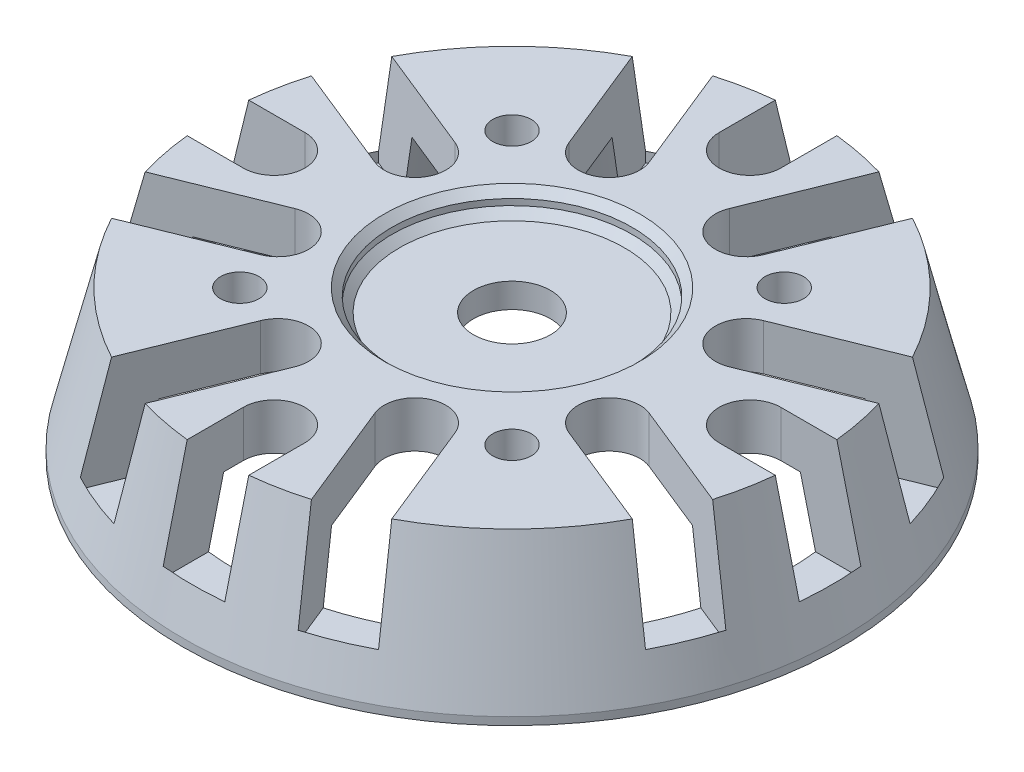
SolidWorks part; units mm, degrees
ref_plane "前视基准面" through (0, 0, 0) normal (0, 0, 1) x (1, 0, 0)
ref_plane "上视基准面" through (0, 0, 0) normal (0, 1, 0) x (1, 0, 0)
ref_plane "右视基准面" through (0, 0, 0) normal (1, 0, 0) x (0, 0, -1)
sketch "草图1" plane through (0, 0, 0) normal (0, 1, 0) x (1, 0, 0)
  circle A0 centre (0, 0) radius 21.4
  dimension "D1" = 42.8
extrude "凸台-拉伸2" add sketch "草图1" along normal blind 0.5 contours A0
sketch "草图3" plane through (0, 0.5, 0) normal (0, 1, 0) x (1, 0, 0)
  circle A0 centre (0, 0) radius 21.4
ref_plane "基准面1" through (0, 9.5, 0) normal (0, 1, 0) x (1, 0, 0)
sketch "草图6" plane through (0, 9.5, 0) normal (0, 1, 0) x (1, 0, 0)
  circle A0 centre (0, 0) radius 19.2
  dimension "D1" = 38.4
loft "放样1" add profiles "草图6" section "草图6" section face at (0, 0.5, 21.4)
shell "抽壳1" thickness 3
sketch "草图7" plane through (0, 9.5, 0) normal (0, 1, 0) x (1, 0, 0)
  circle A0 centre (0, 0) radius 2.5
  dimension "D1" = 5
extrude "切除-拉伸1" cut sketch "草图7" against normal through all
sketch "草图8" plane through (0, 9.5, 0) normal (0, 1, 0) x (1, 0, 0)
  circle A0 centre (0, 0) radius 7.8
  dimension "D1" = 15.6
extrude "切除-拉伸2" cut sketch "草图8" against normal blind 1.4
chamfer "倒角1" distance 0.5 angle 45 2 edges at (0, 9.5, 7.8) (0, 8.1, 7.8)
sketch "草图9" plane through (0, 9.5, 0) normal (0, 1, 0) x (1, 0, 0)
  line L3 (-2, 15.4514) -> (-2, 20.6534)
  line L4 (2, 15.4514) -> (2, 20.6534)
  line L5 (2.6017, 11.5071) -> (5.9818, 19.8691)
  line L6 (6.3102, 10.0081) -> (9.683, 18.3522)
  line L7 (-2.6017, 11.5071) -> (-5.9818, 19.8691)
  line L8 (-6.3102, 10.0081) -> (-9.683, 18.3522)
  line L9 (15.4514, 2) -> (20.6534, 2)
  line L10 (15.4514, -2) -> (20.6534, -2)
  line L11 (11.5071, 2.6017) -> (19.8691, 5.9818)
  line L12 (10.0081, 6.3102) -> (18.3522, 9.683)
  line L13 (11.5071, -2.6017) -> (19.8691, -5.9818)
  line L14 (10.0081, -6.3102) -> (18.3522, -9.683)
  line L15 (2, -15.4514) -> (2, -20.6534)
  line L16 (-2, -15.4514) -> (-2, -20.6534)
  line L17 (2.6017, -11.5071) -> (5.9818, -19.8691)
  line L18 (6.3102, -10.0081) -> (9.683, -18.3522)
  line L19 (-2.6017, -11.5071) -> (-5.9818, -19.8691)
  line L20 (-6.3102, -10.0081) -> (-9.683, -18.3522)
  line L21 (-15.4514, -2) -> (-20.6534, -2)
  line L22 (-15.4514, 2) -> (-20.6534, 2)
  line L23 (-11.5071, -2.6017) -> (-19.8691, -5.9818)
  line L24 (-10.0081, -6.3102) -> (-18.3522, -9.683)
  line L25 (-11.5071, 2.6017) -> (-19.8691, 5.9818)
  line L26 (-10.0081, 6.3102) -> (-18.3522, 9.683)
  arc A0 (-19.8691, -5.9818) -> (-18.3522, -9.683) centre (0, 0) ccw
  arc A1 (-2, 15.4514) -> (2, 15.4514) centre (0, 15.4514) ccw
  arc A2 (2.6017, 11.5071) -> (6.3102, 10.0081) centre (4.4559, 10.7576) ccw
  arc A3 (-2.6017, 11.5071) -> (-6.3102, 10.0081) centre (-4.4559, 10.7576) cw
  arc A4 (15.4514, 2) -> (15.4514, -2) centre (15.4514, 0) ccw
  arc A5 (11.5071, 2.6017) -> (10.0081, 6.3102) centre (10.7576, 4.4559) cw
  arc A6 (11.5071, -2.6017) -> (10.0081, -6.3102) centre (10.7576, -4.4559) ccw
  arc A7 (2, -15.4514) -> (-2, -15.4514) centre (0, -15.4514) ccw
  arc A8 (2.6017, -11.5071) -> (6.3102, -10.0081) centre (4.4559, -10.7576) cw
  arc A9 (-2.6017, -11.5071) -> (-6.3102, -10.0081) centre (-4.4559, -10.7576) ccw
  arc A10 (-15.4514, -2) -> (-15.4514, 2) centre (-15.4514, 0) ccw
  arc A11 (-11.5071, -2.6017) -> (-10.0081, -6.3102) centre (-10.7576, -4.4559) cw
  arc A12 (-11.5071, 2.6017) -> (-10.0081, 6.3102) centre (-10.7576, 4.4559) ccw
  arc A13 (-20.6534, 2) -> (-20.6534, -2) centre (0, 0) ccw
  arc A14 (-9.683, -18.3522) -> (-5.9818, -19.8691) centre (0, 0) ccw
  arc A15 (-2, -20.6534) -> (2, -20.6534) centre (0, 0) ccw
  arc A16 (5.9818, -19.8691) -> (9.683, -18.3522) centre (0, 0) ccw
  arc A17 (18.3522, -9.683) -> (19.8691, -5.9818) centre (0, 0) ccw
  arc A18 (20.6534, -2) -> (20.6534, 2) centre (0, 0) ccw
  arc A19 (19.8691, 5.9818) -> (18.3522, 9.683) centre (0, 0) ccw
  arc A20 (9.683, 18.3522) -> (5.9818, 19.8691) centre (0, 0) ccw
  arc A21 (2, 20.6534) -> (-2, 20.6534) centre (0, 0) ccw
  arc A22 (-5.9818, 19.8691) -> (-9.683, 18.3522) centre (0, 0) ccw
  arc A23 (-18.3522, 9.683) -> (-19.8691, 5.9818) centre (0, 0) ccw
  point P69 (0, 0)
  dimension "D2" = 41.5
  dimension "D3" = 2
  dimension "D4" = 2
  dimension "D1" = 4
  dimension "D5" = 9
  dimension "D7" = 4
extrude "切除-拉伸11" cut sketch "草图9" against normal blind 7
sketch "草图10" plane through (0, 9.5, 0) normal (0, 1, 0) x (1, 0, 0)
  circle A0 centre (0, 0) radius 12.5 construction
  circle A1 centre (8.8388, 8.8388) radius 1.5
  circle A2 centre (8.8388, -8.8388) radius 1.5
  circle A3 centre (-8.8388, -8.8388) radius 1.5
  circle A4 centre (-8.8388, 8.8388) radius 1.5
  point P14 (0, 0)
  dimension "D1" = 25
  dimension "D3" = 3
  dimension "D2" = 4
hole_wizard "M3 螺纹孔的螺纹孔钻头1" positions "3D草图1" profile "草图11" hole size "M3" standard "GB" end condition through all
sketch3d "3D草图1"
  point P0 (-8.8388, 9.5, 8.8388)
  point P3 (8.8388, 9.5, 8.8388)
  point P6 (8.8388, 9.5, -8.8388)
  point P9 (-8.8388, 9.5, -8.8388)
sketch "草图11" plane through (-8.8388, 9.5, 8.8388) normal (1, 0, 0) x (0, 0, 1)
  line L0 (0, 0) -> (0, 9.5)
  line L1 (0, 9.5) -> (1.25, 9.5)
  line L2 (1.25, 9.5) -> (1.25, 0)
  line L5 (1.25, 0) -> (0, 0)
  line L11 (0, -6.35) -> (0, 107.95) construction
  dimension "通孔孔直径" = 2.5
  dimension "通孔孔深度" = 9.5
